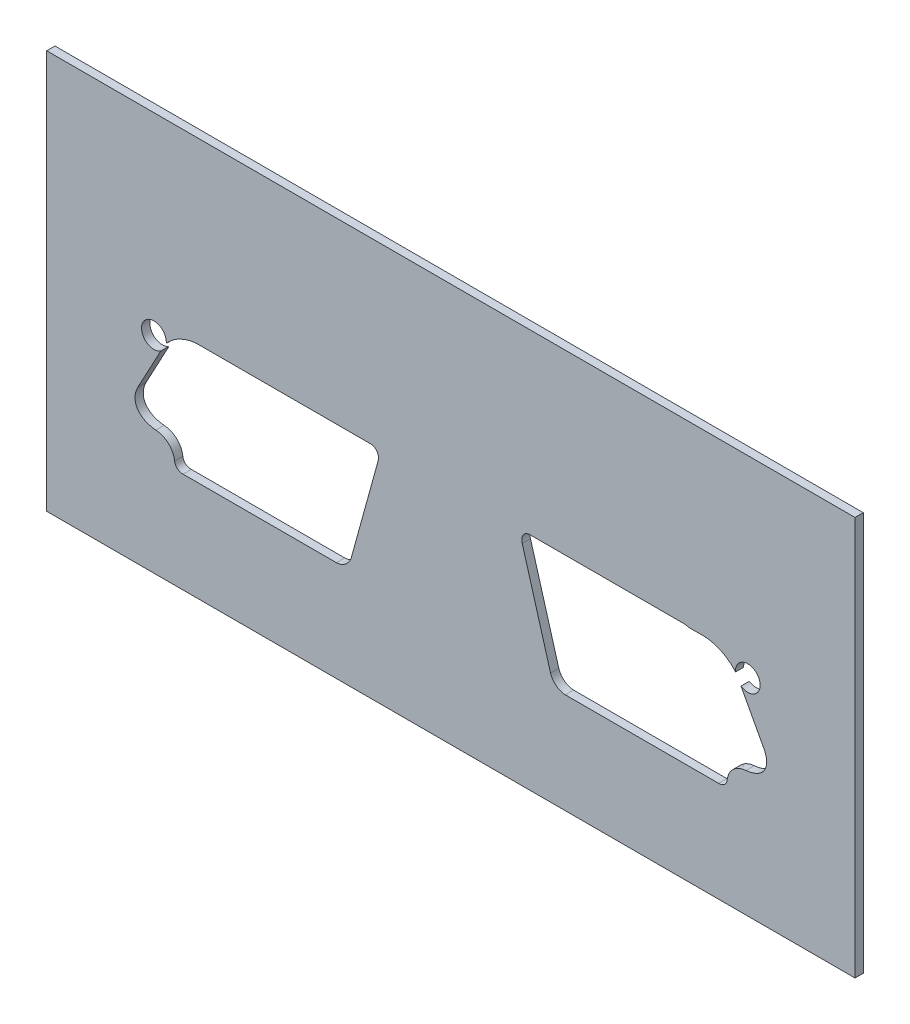
SolidWorks part; units mm, degrees
ref_plane "Спереди" through (0, 0, 0) normal (0, 0, 1) x (1, 0, 0)
ref_plane "Сверху" through (0, 0, 0) normal (0, 1, 0) x (1, 0, 0)
ref_plane "Справа" through (0, 0, 0) normal (1, 0, 0) x (0, 0, -1)
sketch "Эскиз1" plane through (0, 0, 0) normal (0, 0, 1) x (1, 0, 0)
  line L1 (-49, 5.8392) -> (-49, -22.5167)
  line L2 (-49, -22.5167) -> (49, -22.5167)
  line L3 (49, 5.8392) -> (49, -22.5167)
  line L6 (49, 26.4822) -> (49, 5.1962) construction
  line L8 (-49, 5.8392) -> (-49, 15.8392)
  line L9 (-49, 15.8392) -> (49, 15.8392)
  line L10 (49, 5.8392) -> (49, 15.8392)
extrude "Бобышка-Вытянуть1" add sketch "Эскиз1" along normal blind 1
sketch "Эскиз2" plane through (0, 0, 0) normal (0, 0, -1) x (-1, 0, 0)
  line L0 (27.2261, -9.1221) -> (15.7399, -9.1221)
  line L1 (14.9178, -10.1567) -> (17.4421, -18.9309)
  line L2 (19.1226, -20.331) -> (30.8268, -20.331)
  line L3 (31.6433, -19.2954) -> (29.101, -10.4886)
  line L4 (0, 0) -> (0, -19.7017) construction
  line L5 (-31.6433, -19.2954) -> (-29.101, -10.4886)
  line L6 (-19.1226, -20.331) -> (-30.8268, -20.331)
  line L7 (-14.9178, -10.1567) -> (-17.4421, -18.9309)
  line L8 (-27.2261, -9.1221) -> (-15.7399, -9.1221)
  arc A0 (15.7399, -9.1221) -> (14.9178, -10.1567) centre (15.8146, -10.0254) ccw
  arc A1 (17.4421, -18.9309) -> (19.1226, -20.331) centre (19.2232, -18.5017) ccw
  arc A2 (30.8268, -20.331) -> (31.6433, -19.2954) centre (30.7494, -19.4304) ccw
  arc A3 (29.101, -10.4886) -> (27.2261, -9.1221) centre (27.3312, -10.9473) ccw
  arc A4 (-29.101, -10.4886) -> (-27.2261, -9.1221) centre (-27.3312, -10.9473) cw
  arc A5 (-30.8268, -20.331) -> (-31.6433, -19.2954) centre (-30.7494, -19.4304) cw
  arc A6 (-17.4421, -18.9309) -> (-19.1226, -20.331) centre (-19.2232, -18.5017) cw
  arc A7 (-15.7399, -9.1221) -> (-14.9178, -10.1567) centre (-15.8146, -10.0254) cw
extrude "Вырез-Вытянуть4" cut sketch "Эскиз2" against normal through all
sketch "Эскиз4" plane through (0, 0, 0) normal (0, 0, -1) x (-1, 0, 0)
  circle A0 centre (36, -7.525) radius 1.5
  circle A1 centre (-36, -7.525) radius 1.5
extrude "Вырез-Вытянуть5" cut sketch "Эскиз4" against normal through all
sketch "Sketch3" plane through (0, 0, 1) normal (0, 0, 1) x (1, 0, 0)
  line L4 (-35.1709, -8.775) -> (-37.9251, -13.9067)
  line L5 (8.6523, -7.0681) -> (12.0857, -18.9615)
  line L6 (28.2287, -5.6825) -> (9.638, -5.6825)
  line L7 (30.6309, -5.7832) -> (28.7783, -5.7839)
  line L8 (37.9106, -13.8798) -> (35.1709, -8.775)
  line L9 (13.8713, -20.3472) -> (32.462, -20.3472)
  line L10 (8.6523, -7.0681) -> (12.0857, -18.9615)
  line L11 (28.2287, -5.6825) -> (9.638, -5.6825)
  line L12 (30.6309, -5.7832) -> (28.7783, -5.7839)
  line L13 (37.9106, -13.8798) -> (35.1709, -8.775)
  line L14 (13.8713, -20.3472) -> (32.462, -20.3472)
  line L15 (-9.8219, -5.7989) -> (-30.645, -5.807)
  line L16 (-12.0807, -18.9439) -> (-8.8308, -7.1669)
  line L17 (-32.462, -20.3472) -> (-13.8713, -20.3472)
  line L18 (-35.1709, -8.775) -> (-37.9251, -13.9067)
  line L19 (-9.8219, -5.7989) -> (-30.645, -5.807)
  line L20 (-12.0807, -18.9439) -> (-8.8308, -7.1669)
  line L21 (-32.462, -20.3472) -> (-13.8713, -20.3472)
  arc A2 (34.5043, -7.6389) -> (34.5716, -7.9829) centre (36, -7.525) ccw
  arc A3 (34.5716, -7.9829) -> (35.1709, -8.775) centre (36, -7.525) ccw
  arc A4 (34.5043, -7.6389) -> (34.5716, -7.9829) centre (36, -7.525) ccw
  arc A5 (34.5716, -7.9829) -> (35.1709, -8.775) centre (36, -7.525) ccw
  arc A6 (-35.1709, -8.775) -> (-34.5791, -8.0058) centre (-36, -7.525) ccw
  arc A7 (-34.5791, -8.0058) -> (-34.5051, -7.6482) centre (-36, -7.525) ccw
  arc A8 (-35.1709, -8.775) -> (-34.5791, -8.0058) centre (-36, -7.525) ccw
  arc A9 (-34.5791, -8.0058) -> (-34.5051, -7.6482) centre (-36, -7.525) ccw
  ellipse E5 centre (10.038, -7.0681) end of major axis (8.8285, -6.0207) minor radius 1.2 (9.638, -5.6825) -> (8.6523, -7.0681) ccw
  ellipse E6 centre (28.6287, -7.0681) end of major axis (27.4192, -6.0207) minor radius 1.2 (28.7783, -5.7839) -> (28.2287, -5.6825) ccw
  ellipse E7 centre (31.8702, -8.0919) end of major axis (28.7995, -6.6629) minor radius 2 (34.5043, -7.6389) -> (30.6309, -5.7832) ccw
  ellipse E8 centre (32.062, -18.9615) end of major axis (30.8525, -17.9141) minor radius 1.2 (32.462, -20.3472) -> (33.4962, -19.4843) ccw
  ellipse E9 centre (13.4713, -18.9615) end of major axis (12.2618, -17.9141) minor radius 1.2 (12.0857, -18.9615) -> (13.8713, -20.3472) ccw
  ellipse E10 centre (10.038, -7.0681) end of major axis (8.8285, -6.0207) minor radius 1.2 (9.638, -5.6825) -> (8.6523, -7.0681) ccw
  ellipse E11 centre (28.6287, -7.0681) end of major axis (27.4192, -6.0207) minor radius 1.2 (28.7783, -5.7839) -> (28.2287, -5.6825) ccw
  ellipse E12 centre (31.8702, -8.0919) end of major axis (28.7995, -6.6629) minor radius 2 (34.5043, -7.6389) -> (30.6309, -5.7832) ccw
  ellipse E13 centre (32.062, -18.9615) end of major axis (30.8525, -17.9141) minor radius 1.2 (32.462, -20.3472) -> (33.4962, -19.4843) ccw
  ellipse E14 centre (13.4713, -18.9615) end of major axis (12.2618, -17.9141) minor radius 1.2 (12.0857, -18.9615) -> (13.8713, -20.3472) ccw
  ellipse E15 centre (-31.8835, -8.1166) end of major axis (-28.8122, -6.6856) minor radius 2 (-30.645, -5.807) -> (-34.5051, -7.6482) ccw
  ellipse E16 centre (-10.2214, -7.1846) end of major axis (-9.0119, -6.1371) minor radius 1.2 (-8.8308, -7.1669) -> (-9.8219, -5.7989) ccw
  ellipse E17 centre (-13.4713, -18.9615) end of major axis (-12.2618, -17.9141) minor radius 1.2 (-13.8713, -20.3472) -> (-12.0807, -18.9439) ccw
  ellipse E18 centre (-32.062, -18.9615) end of major axis (-30.8525, -17.9141) minor radius 1.2 (-33.4952, -19.4922) -> (-32.462, -20.3472) ccw
  ellipse E19 centre (-37.0781, -20.8189) end of major axis (-34.0544, -18.2003) minor radius 3 (-33.4952, -19.4922) -> (-35.7663, -17.3693) ccw
  ellipse E20 centre (-31.8835, -8.1166) end of major axis (-28.8122, -6.6856) minor radius 2 (-30.645, -5.807) -> (-34.5051, -7.6482) ccw
  ellipse E21 centre (-10.2214, -7.1846) end of major axis (-9.0119, -6.1371) minor radius 1.2 (-8.8308, -7.1669) -> (-9.8219, -5.7989) ccw
  ellipse E22 centre (-13.4713, -18.9615) end of major axis (-12.2618, -17.9141) minor radius 1.2 (-13.8713, -20.3472) -> (-12.0807, -18.9439) ccw
  ellipse E23 centre (-32.062, -18.9615) end of major axis (-30.8525, -17.9141) minor radius 1.2 (-33.4952, -19.4922) -> (-32.462, -20.3472) ccw
  ellipse E24 centre (-37.0781, -20.8189) end of major axis (-34.0544, -18.2003) minor radius 3 (-33.4952, -19.4922) -> (-35.7663, -17.3693) ccw
  spline S1 degree 3 poles (-3612.3196, -1806.8838) (141.1066, -20.6987) (-32.5994, 3.1691) (-38.2359, -14.6873) (-38.2784, -14.8959) (-38.2974, -15.2122) (-38.2963, -15.3175) (-38.2774, -15.5276) (-38.2593, -15.6333) (-38.206, -15.8369) (-38.1708, -15.9356) (-38.0829, -16.1267) (-38.0295, -16.2198) (-37.8491, -16.4795) (-37.6989, -16.6311) (-37.3628, -16.8865) (-37.1797, -16.9895) (-17.2345, -25.642) (53.9483, 176.5986) (-943.5135, -3912.4154) knots -10.923116 -10.923116 -10.923116 -10.923116 0.125 0.125 0.25 0.25 0.3125 0.3125 0.375 0.375 0.4375 0.4375 0.5 0.5 0.625 0.625 0.75 0.75 13.437928 13.437928 13.437928 13.437928 only from (-37.9251, -13.9067) to (-35.7663, -17.3693)
  spline S2 degree 3 poles (2061.9964, -3465.9377) (-69.0178, 170.9177) (17.3944, -25.618) (37.1704, -16.959) (37.355, -16.8543) (37.6875, -16.5998) (37.8383, -16.4466) (38.0766, -16.1015) (38.1662, -15.9056) (38.2715, -15.4997) (38.2888, -15.2855) (38.2633, -14.8675) (38.2207, -14.6579) (31.82, 5.5764) (-180.6478, -51.2528) (3762.9572, 1441.6708) knots -12.455389 -12.455389 -12.455389 -12.455389 0.25 0.25 0.375 0.375 0.5 0.5 0.625 0.625 0.75 0.75 0.875 0.875 13.404708 13.404708 13.404708 13.404708 only from (35.7615, -17.3421) to (37.9106, -13.8798)
  spline S3 degree 3 poles (203.5774, 3973.3026) (187.7595, -140.5035) (26.2256, -34.1242) (33.8533, -18.4172) (34.0253, -18.1839) (34.4362, -17.8036) (34.6819, -17.6499) (51.4194, -10.709) (148.6693, -173.0193) (-3938.8197, 407.6381) knots -15.007963 -15.007963 -15.007963 -15.007963 0.25 0.25 0.5 0.5 0.75 0.75 16.651429 16.651429 16.651429 16.651429 only from (33.4962, -19.4843) to (35.7615, -17.3421)
  spline S4 degree 3 poles (35.7615, -17.3421) (36.1812, -17.3014) (36.5924, -17.2121) (37.1704, -16.959) (37.355, -16.8543) (37.6875, -16.5998) (37.8383, -16.4466) (38.0766, -16.1015) (38.1662, -15.9056) (38.2715, -15.4997) (38.2888, -15.2855) (38.2633, -14.8675) (38.2207, -14.6579) (38.0943, -14.2582) (38.0105, -14.066) (37.9106, -13.8798) knots 0 0 0 0 0.25 0.25 0.375 0.375 0.5 0.5 0.625 0.625 0.75 0.75 0.875 0.875 1 1 1 1
  spline S5 degree 3 poles (33.4962, -19.4843) (33.5297, -19.2012) (33.6073, -18.9236) (33.8533, -18.4172) (34.0253, -18.1839) (34.4362, -17.8036) (34.6819, -17.6499) (35.2, -17.4351) (35.4791, -17.3694) (35.7615, -17.3421) knots 0 0 0 0 0.25 0.25 0.5 0.5 0.75 0.75 1 1 1 1
  spline S6 degree 3 poles (-37.9251, -13.9067) (-38.0252, -14.0933) (-38.1098, -14.2878) (-38.2359, -14.6873) (-38.2784, -14.8959) (-38.2974, -15.2122) (-38.2963, -15.3175) (-38.2774, -15.5276) (-38.2593, -15.6333) (-38.206, -15.8369) (-38.1708, -15.9356) (-38.0829, -16.1267) (-38.0295, -16.2198) (-37.8491, -16.4795) (-37.6989, -16.6311) (-37.3628, -16.8865) (-37.1797, -16.9895) (-36.5959, -17.2427) (-36.1868, -17.3297) (-35.7663, -17.3693) knots 0 0 0 0 0.125 0.125 0.25 0.25 0.3125 0.3125 0.375 0.375 0.4375 0.4375 0.5 0.5 0.625 0.625 0.75 0.75 1 1 1 1
  dimension "D1" = 0
  dimension "D2" = 0
extrude "Cut-Extrude1" cut sketch "Sketch3" against normal up to surface (1 mm away) up to face at (-37.5, -7.525, 0)
sketch "Sketch4" plane through (0, 0, 1) normal (0, 0, 1) x (1, 0, 0)
  line L0 (49, -22.5167) -> (49, 15.8392) construction
  line L1 (-49, -22.5167) -> (49, -22.5167)
  line L2 (-49, -22.5167) -> (-49, -32.5167)
  line L3 (-49, -32.5167) -> (49, -32.5167)
  line L4 (49, -22.5167) -> (49, -32.5167)
  dimension "D1" = 0
  dimension "D2" = 10
extrude "Boss-Extrude1" add sketch "Sketch4" against normal blind 1
